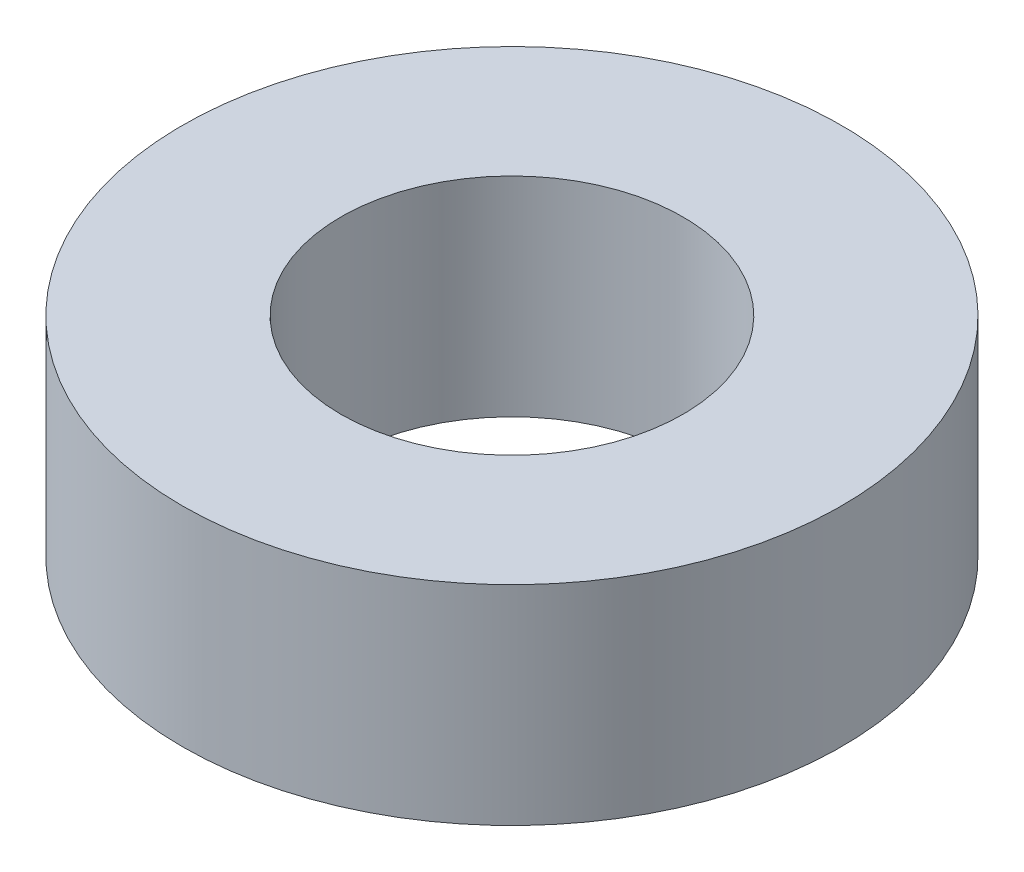
SolidWorks part; units mm, degrees
ref_plane "Front Plane" through (0, 0, 0) normal (0, 0, 1) x (1, 0, 0)
ref_plane "Top Plane" through (0, 0, 0) normal (0, 1, 0) x (1, 0, 0)
ref_plane "Right Plane" through (0, 0, 0) normal (1, 0, 0) x (0, 0, -1)
sketch "Sketch1" plane through (0, 0, 0) normal (0, 1, 0) x (1, 0, 0)
  circle A0 centre (0, 0) radius 7.9
  circle A1 centre (0, 0) radius 4.1
  dimension "D1" = 15.8
  dimension "D2" = 8.2
extrude "Boss-Extrude1" add sketch "Sketch1" along normal blind 5
